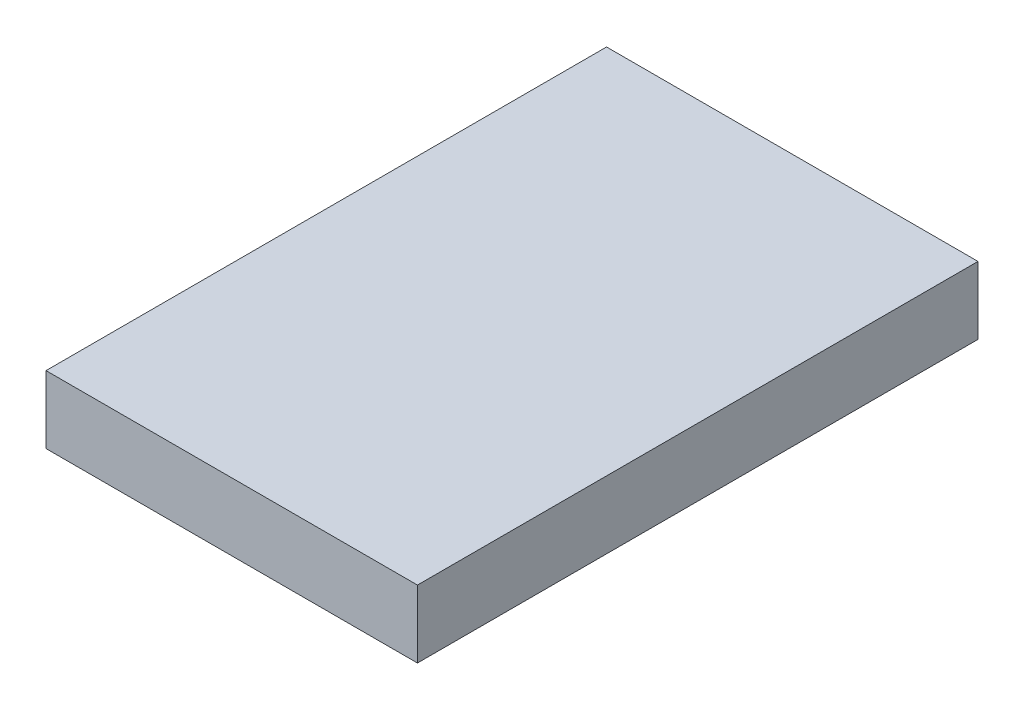
SolidWorks part; units mm, degrees
ref_plane "Front Plane" through (0, 0, 0) normal (0, 0, 1) x (1, 0, 0)
ref_plane "Top Plane" through (0, 0, 0) normal (0, 1, 0) x (1, 0, 0)
ref_plane "Right Plane" through (0, 0, 0) normal (1, 0, 0) x (0, 0, -1)
sketch "Sketch1" plane through (0, 0, 0) normal (0, 1, 0) x (1, 0, 0)
  line L1 (-27.5, -41.5) -> (27.5, -41.5)
  line L2 (-27.5, -41.5) -> (-27.5, 41.5)
  line L3 (-27.5, 41.5) -> (27.5, 41.5)
  line L4 (27.5, -41.5) -> (27.5, 41.5)
  line L5 (-27.5, -41.5) -> (27.5, 41.5) construction
  line L6 (-27.5, 41.5) -> (27.5, -41.5) construction
  point P0 (0, 0)
  dimension "D1" = 83
  dimension "D2" = 55
extrude "Boss-Extrude1" add sketch "Sketch1" along normal blind 10
